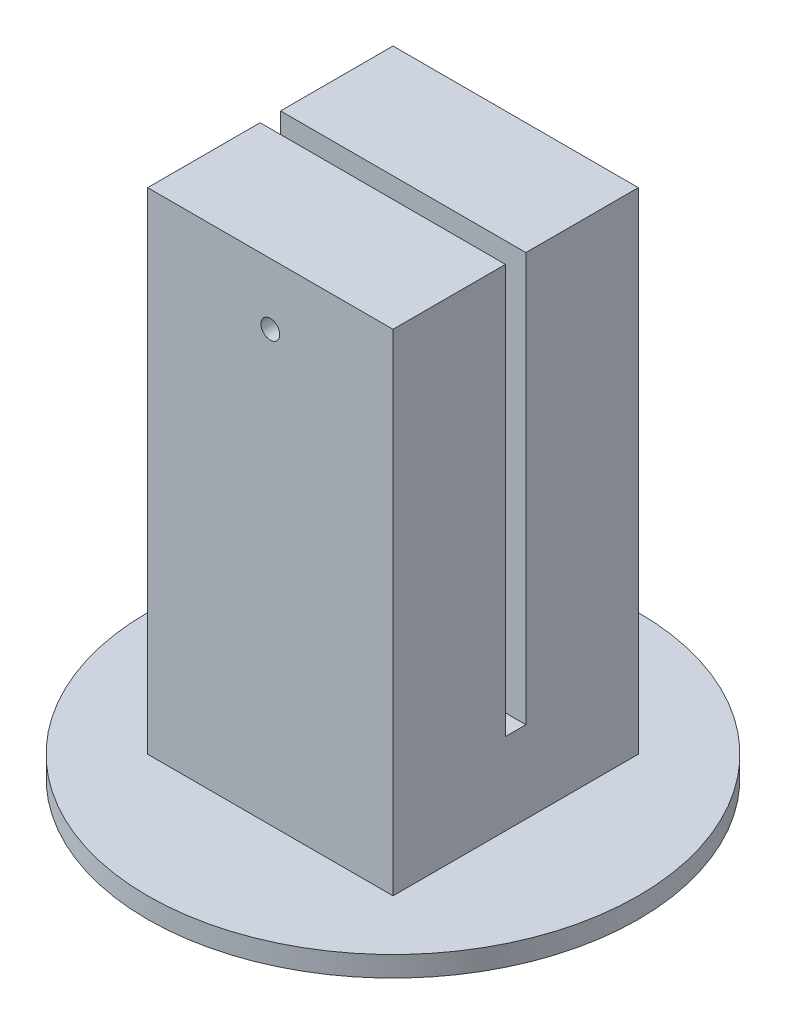
SolidWorks part; units mm, degrees
ref_plane "Front Plane" through (0, 0, 0) normal (0, 0, 1) x (1, 0, 0)
ref_plane "Top Plane" through (0, 0, 0) normal (0, 1, 0) x (1, 0, 0)
ref_plane "Right Plane" through (0, 0, 0) normal (1, 0, 0) x (0, 0, -1)
sketch "Sketch1" plane through (0, 0, 0) normal (0, 1, 0) x (1, 0, 0)
  circle A0 centre (0, 0) radius 38.1
  dimension "D1" = 76.2
extrude "Boss-Extrude1" add sketch "Sketch1" along normal blind 3.175
sketch "Sketch2" plane through (0, 3.175, 0) normal (0, 1, 0) x (1, 0, 0)
  line L1 (-19.05, -19.05) -> (19.05, -19.05)
  line L2 (-19.05, -19.05) -> (-19.05, 19.05)
  line L3 (-19.05, 19.05) -> (19.05, 19.05)
  line L4 (19.05, -19.05) -> (19.05, 19.05)
  line L5 (-19.05, -19.05) -> (19.05, 19.05) construction
  line L6 (-19.05, 19.05) -> (19.05, -19.05) construction
  point P0 (0, 0)
  dimension "D1" = 38.1
  dimension "D2" = 38.1
extrude "Boss-Extrude3" add sketch "Sketch2" along normal blind 76.2
sketch "Sketch5" plane through (-19.05, 0, 0) normal (-1, 0, 0) x (0, 0, 1)
  line L0 (0, 79.375) -> (-1.5875, 79.375)
  line L1 (-19.05, 79.375) -> (19.05, 79.375) construction
  line L2 (-1.5875, 79.375) -> (-1.5875, 15.875)
  line L3 (-1.5875, 15.875) -> (1.5875, 15.875)
  line L4 (1.5875, 15.875) -> (1.5875, 79.375)
  line L5 (1.5875, 79.375) -> (0, 79.375)
  dimension "D1" = 63.5
  dimension "D2" = 1.5875
  dimension "D3" = 1.5875
extrude "Cut-Extrude1" cut sketch "Sketch5" against normal through all
sketch "Sketch6" plane through (0, 0, 19.05) normal (0, 0, 1) x (1, 0, 0)
  line L0 (-19.05, 79.375) -> (19.05, 79.375) construction
  circle A0 centre (0, 69.85) radius 1.4605
  dimension "D2" = 2.921
  dimension "D1" = 9.525
extrude "Cut-Extrude2" cut sketch "Sketch6" against normal through all
